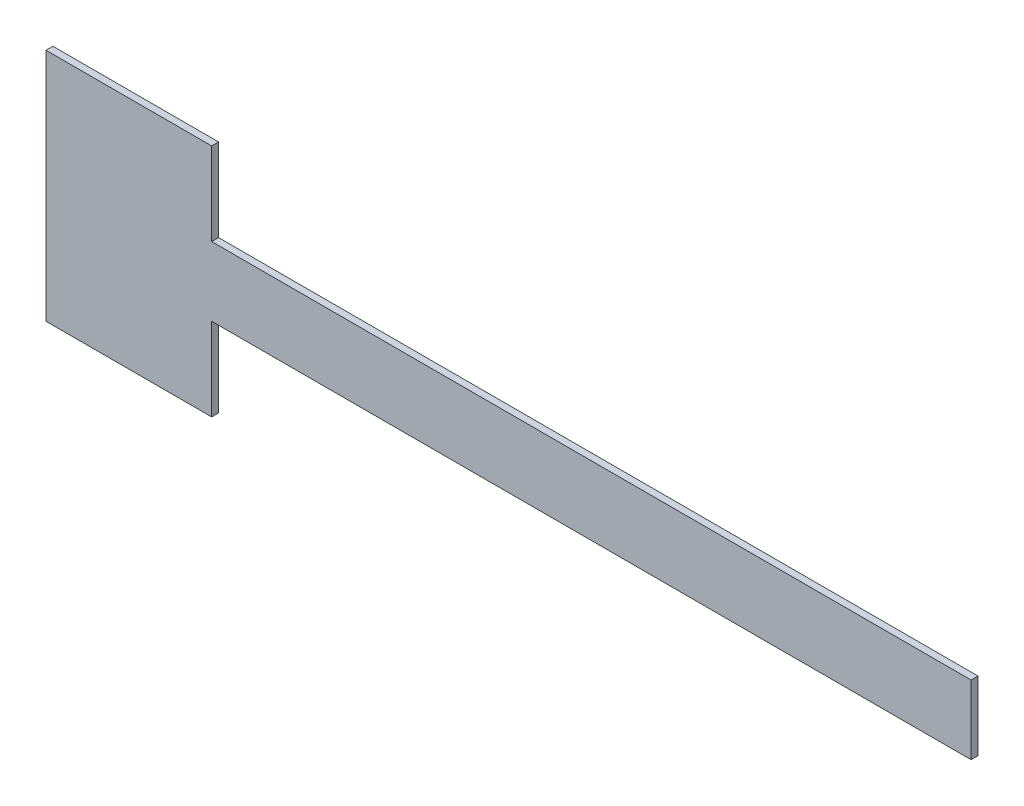
SolidWorks part; units mm, degrees
ref_plane "Alzado" through (0, 0, 0) normal (0, 0, 1) x (1, 0, 0)
ref_plane "Planta" through (0, 0, 0) normal (0, 1, 0) x (1, 0, 0)
ref_plane "Vista lateral" through (0, 0, 0) normal (1, 0, 0) x (0, 0, -1)
sketch "Croquis1" plane through (0, 0, 0) normal (0, 0, 1) x (1, 0, 0)
  line L0 (67, 8.5) -> (0, 8.5) construction
  line L1 (0, 0) -> (12, 0)
  line L2 (0, 0) -> (0, 17)
  line L3 (0, 17) -> (12, 17)
  line L4 (12, 0) -> (12, 6)
  line L5 (12, 11) -> (67, 11)
  line L7 (12, 6) -> (67, 6)
  line L8 (67, 11) -> (67, 6)
  line L9 (12, 11) -> (12, 17)
  dimension "D1" = 55
  dimension "D2" = 17
  dimension "D3" = 12
  dimension "D4" = 5
extrude "Saliente-Extruir1" add sketch "Croquis1" along normal blind 0.5
